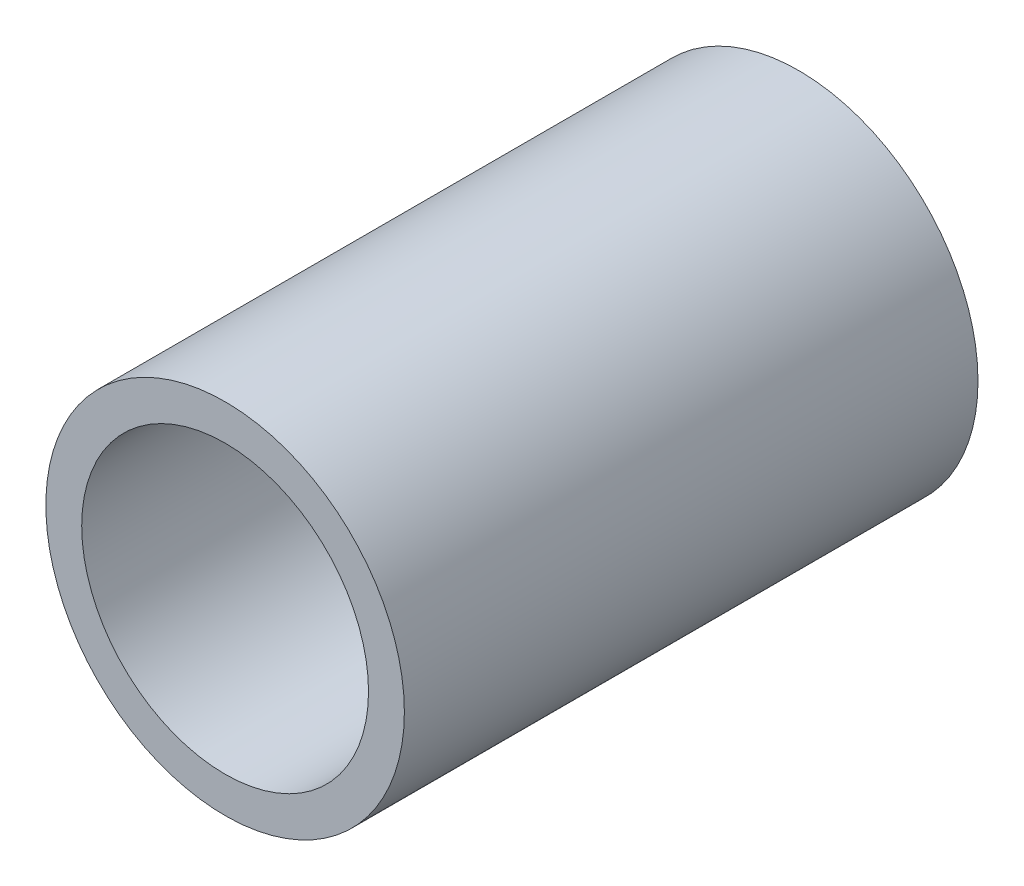
SolidWorks part; units mm, degrees
ref_plane "Front Plane" through (0, 0, 0) normal (1, 0, 0) x (0, 1, 0)
ref_plane "Top Plane" through (0, 0, 0) normal (0, 0, 1) x (0, 1, 0)
ref_plane "Right Plane" through (0, 0, 0) normal (0, 1, 0) x (-1, 0, 0)
sketch "Sketch1" plane through (0, 0, 0) normal (0, 0, 1) x (0, 1, 0)
  circle A0 centre (0, 0) radius 7.5
  circle A1 centre (0, 0) radius 6
  dimension "D1" = 15
  dimension "D2" = 12
extrude "Boss-Extrude1" add sketch "Sketch1" along normal mid plane 24
